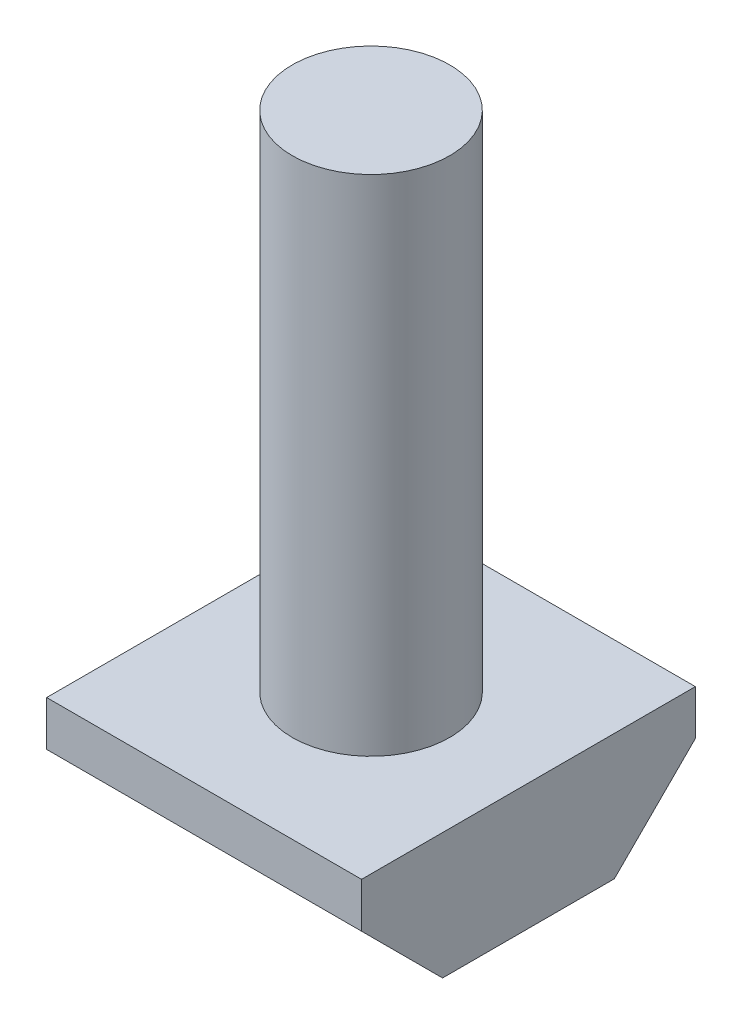
SolidWorks part; units mm, degrees
ref_plane "Front Plane" through (0, 0, 0) normal (0, 0, 1) x (1, 0, 0)
ref_plane "Top Plane" through (0, 0, 0) normal (0, 1, 0) x (1, 0, 0)
ref_plane "Right Plane" through (0, 0, 0) normal (1, 0, 0) x (0, 0, -1)
sketch "Sketch1" plane through (0, 0, 0) normal (1, 0, 0) x (0, 0, -1)
  line L0 (-19.5112, 9.4934) -> (-14.0568, 9.4934)
  line L1 (-14.0568, 9.4934) -> (-11.484, 12.0662)
  line L2 (-11.484, 12.0662) -> (-11.484, 13.4934)
  line L3 (-11.484, 13.4934) -> (-13.684, 13.4934)
  line L4 (-19.884, 13.4934) -> (-22.084, 13.4934)
  line L5 (-22.084, 13.4934) -> (-22.084, 12.0662)
  line L6 (-22.084, 12.0662) -> (-19.5112, 9.4934)
  line L7 (-13.684, 13.4934) -> (-19.884, 13.4934)
extrude "Boss-Extrude1" add sketch "Sketch1" along normal blind 10
sketch "Sketch2" plane through (0, 13.4934, 0) normal (0, 1, 0) x (1, 0, 0)
  line L0 (5, -11.484) -> (5, -22.084)
  line L1 (10, -11.484) -> (0, -11.484) construction
  line L2 (10, -22.084) -> (0, -22.084) construction
  line L3 (5, -22.084) -> (10, -16.784)
  line L4 (10, -11.484) -> (10, -22.084) construction
  line L5 (10, -16.784) -> (0, -16.784)
  line L6 (0, -11.484) -> (0, -22.084) construction
  circle A0 centre (5, -16.784) radius 2.5
  dimension "D1" = 5
extrude "Boss-Extrude2" add sketch "Sketch2" along normal blind 16 contours L5 A0 L0 | L0 A0 L5 | L5 A0 L0 | L0 A0 L5
